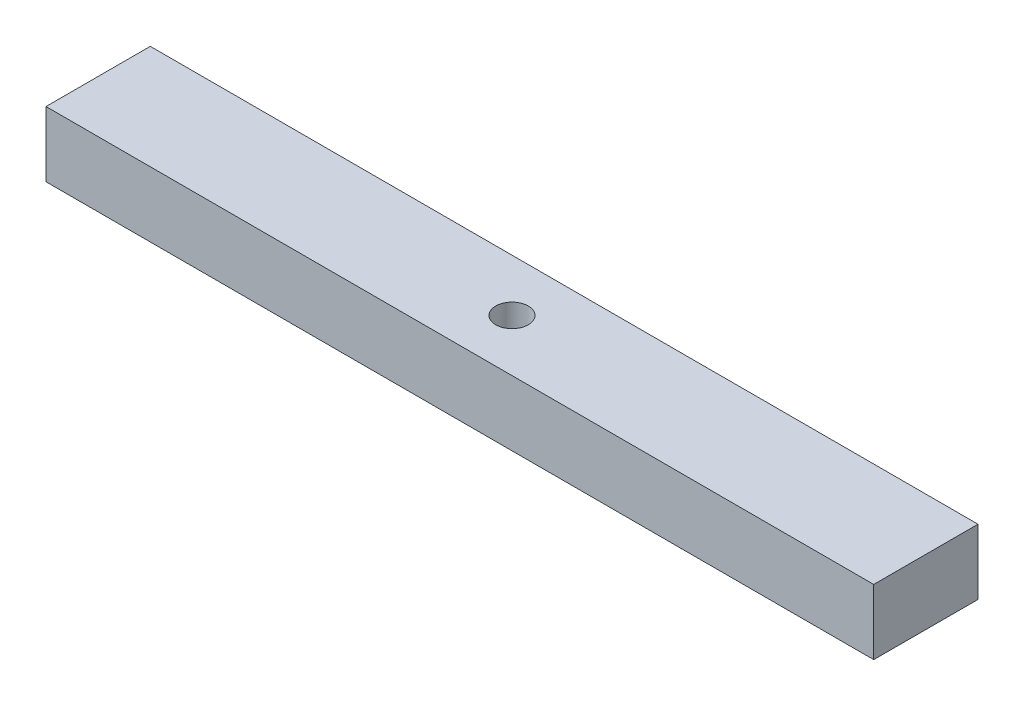
SolidWorks part; units mm, degrees
ref_plane "Front Plane" through (0, 0, 0) normal (0, 0, 1) x (1, 0, 0)
ref_plane "Top Plane" through (0, 0, 0) normal (0, 1, 0) x (1, 0, 0)
ref_plane "Right Plane" through (0, 0, 0) normal (1, 0, 0) x (0, 0, -1)
sketch "Sketch1" plane through (0, 0, 0) normal (0, 1, 0) x (1, 0, 0)
  line L1 (63.5, -8) -> (-63.5, -8)
  line L2 (63.5, -8) -> (63.5, 8)
  line L3 (63.5, 8) -> (-63.5, 8)
  line L4 (-63.5, -8) -> (-63.5, 8)
  line L5 (63.5, -8) -> (-63.5, 8) construction
  line L6 (63.5, 8) -> (-63.5, -8) construction
  circle A0 centre (0, 0) radius 8 construction
  circle A1 centre (0, 0) radius 2.5
  dimension "D1" = 16
  dimension "D2" = 5
  dimension "D3" = 127
extrude "Boss-Extrude1" add sketch "Sketch1" along normal blind 10
